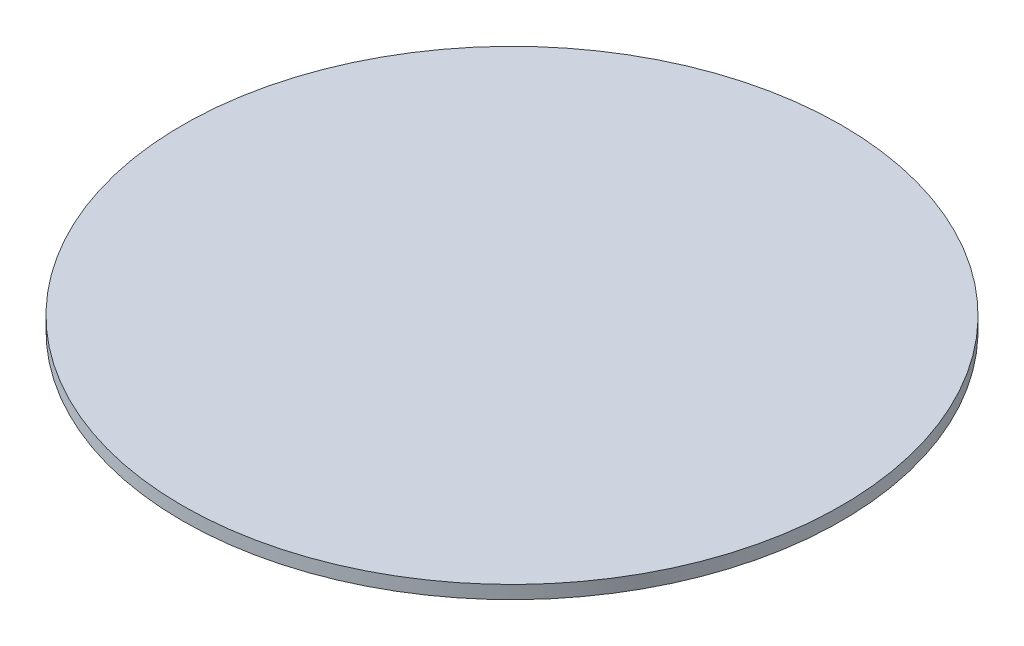
SolidWorks part; units mm, degrees
ref_plane "前视基准面" through (0, 0, 0) normal (0, 0, 1) x (1, 0, 0)
ref_plane "上视基准面" through (0, 0, 0) normal (0, 1, 0) x (1, 0, 0)
ref_plane "右视基准面" through (0, 0, 0) normal (1, 0, 0) x (0, 0, -1)
other "Configuration Table"
sketch "草图1" plane through (0, 0, 0) normal (0, 1, 0) x (1, 0, 0)
  circle A0 centre (0, 0) radius 75
  dimension "D1" = 150
extrude "凸台-拉伸1" add sketch "草图1" along normal blind 3
